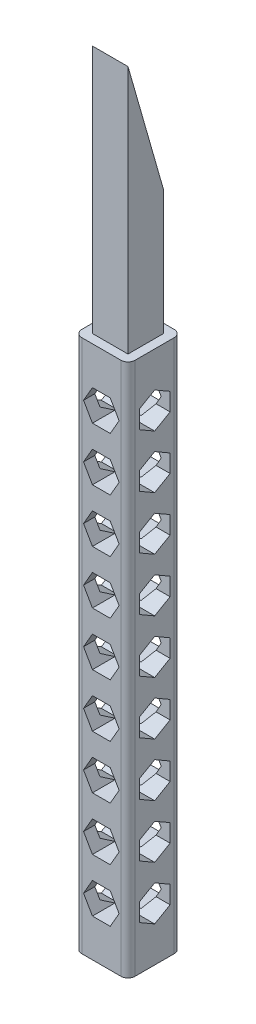
SolidWorks part; units mm, degrees
ref_plane "Front Plane" through (0, 0, 0) normal (0, 0, 1) x (1, 0, 0)
ref_plane "Top Plane" through (0, 0, 0) normal (0, 1, 0) x (1, 0, 0)
ref_plane "Right Plane" through (0, 0, 0) normal (1, 0, 0) x (0, 0, -1)
sketch "Sketch1" plane through (0, 0, 0) normal (0, 1, 0) x (1, 0, 0)
  line L1 (-7.5, -7.5) -> (7.5, -7.5)
  line L2 (-7.5, -7.5) -> (-7.5, 7.5)
  line L3 (-7.5, 7.5) -> (7.5, 7.5)
  line L4 (7.5, -7.5) -> (7.5, 7.5)
  line L5 (-7.5, -7.5) -> (7.5, 7.5) construction
  line L6 (-7.5, 7.5) -> (7.5, -7.5) construction
  point P0 (0, 0)
extrude "Boss-Extrude1" add sketch "Sketch1" along normal blind 150
sketch "Sketch3" plane through (0, 150, 0) normal (0, 1, 0) x (1, 0, 0)
  line L1 (-5, 5) -> (5, 5)
  line L2 (-5, 5) -> (-5, -5)
  line L3 (-5, -5) -> (5, -5)
  line L4 (5, 5) -> (5, -5)
  line L5 (-5, 5) -> (5, -5) construction
  line L6 (-5, -5) -> (5, 5) construction
  point P0 (0, 0)
extrude "Boss-Extrude2" add sketch "Sketch3" along normal blind 70
sketch "Sketch4" plane through (-5, 0, 0) normal (-1, 0, 0) x (0, 0, 1)
  line L0 (-5, 185) -> (5, 220)
  line L1 (-5, 220) -> (-5, 150) construction
  line L2 (-5, 185) -> (-5, 220)
  line L3 (-5, 220) -> (5, 220)
extrude "Cut-Extrude1" cut sketch "Sketch4" against normal blind 70
sketch "Sketch5" plane through (0, 0, -7.5) normal (0, 0, -1) x (-1, 0, 0)
  line L0 (0, 150) -> (0, 0) construction
  line L1 (-7.5, 150) -> (7.5, 150) construction
  line L2 (-7.5, 0) -> (7.5, 0) construction
  line L3 (5, 90) -> (2.5, 94.3301)
  line L4 (5, 75) -> (2.5, 79.3301)
  line L5 (2.5, 79.3301) -> (-2.5, 79.3301)
  line L6 (-2.5, 79.3301) -> (-5, 75)
  line L7 (-5, 75) -> (-2.5, 70.6699)
  line L8 (-2.5, 70.6699) -> (2.5, 70.6699)
  line L9 (2.5, 70.6699) -> (5, 75)
  line L10 (2.5, 94.3301) -> (-2.5, 94.3301)
  line L11 (-2.5, 94.3301) -> (-5, 90)
  line L12 (-5, 90) -> (-2.5, 85.6699)
  line L13 (-2.5, 85.6699) -> (2.5, 85.6699)
  line L14 (2.5, 85.6699) -> (5, 90)
  line L15 (5, 105) -> (2.5, 109.3301)
  line L16 (2.5, 109.3301) -> (-2.5, 109.3301)
  line L17 (-2.5, 109.3301) -> (-5, 105)
  line L18 (-5, 105) -> (-2.5, 100.6699)
  line L19 (-2.5, 100.6699) -> (2.5, 100.6699)
  line L20 (2.5, 100.6699) -> (5, 105)
  line L21 (5, 120) -> (2.5, 124.3301)
  line L22 (2.5, 124.3301) -> (-2.5, 124.3301)
  line L23 (-2.5, 124.3301) -> (-5, 120)
  line L24 (-5, 120) -> (-2.5, 115.6699)
  line L25 (-2.5, 115.6699) -> (2.5, 115.6699)
  line L26 (2.5, 115.6699) -> (5, 120)
  line L27 (5, 135) -> (2.5, 139.3301)
  line L28 (2.5, 139.3301) -> (-2.5, 139.3301)
  line L29 (-2.5, 139.3301) -> (-5, 135)
  line L30 (-5, 135) -> (-2.5, 130.6699)
  line L31 (-2.5, 130.6699) -> (2.5, 130.6699)
  line L32 (2.5, 130.6699) -> (5, 135)
  line L33 (5, 60) -> (2.5, 64.3301)
  line L34 (2.5, 64.3301) -> (-2.5, 64.3301)
  line L35 (-2.5, 64.3301) -> (-5, 60)
  line L36 (-5, 60) -> (-2.5, 55.6699)
  line L37 (-2.5, 55.6699) -> (2.5, 55.6699)
  line L38 (2.5, 55.6699) -> (5, 60)
  line L39 (5, 45) -> (2.5, 49.3301)
  line L40 (2.5, 49.3301) -> (-2.5, 49.3301)
  line L41 (-2.5, 49.3301) -> (-5, 45)
  line L42 (-5, 45) -> (-2.5, 40.6699)
  line L43 (-2.5, 40.6699) -> (2.5, 40.6699)
  line L44 (2.5, 40.6699) -> (5, 45)
  line L45 (5, 30) -> (2.5, 34.3301)
  line L46 (2.5, 34.3301) -> (-2.5, 34.3301)
  line L47 (-2.5, 34.3301) -> (-5, 30)
  line L48 (-5, 30) -> (-2.5, 25.6699)
  line L49 (-2.5, 25.6699) -> (2.5, 25.6699)
  line L50 (2.5, 25.6699) -> (5, 30)
  line L51 (5, 15) -> (2.5, 19.3301)
  line L52 (2.5, 19.3301) -> (-2.5, 19.3301)
  line L53 (-2.5, 19.3301) -> (-5, 15)
  line L54 (-5, 15) -> (-2.5, 10.6699)
  line L55 (-2.5, 10.6699) -> (2.5, 10.6699)
  line L56 (2.5, 10.6699) -> (5, 15)
  circle A0 centre (0, 75) radius 4.3301 construction
  circle A1 centre (0, 90) radius 4.3301 construction
  circle A2 centre (0, 105) radius 4.3301 construction
  circle A3 centre (0, 120) radius 4.3301 construction
  circle A4 centre (0, 135) radius 4.3301 construction
  circle A5 centre (0, 60) radius 4.3301 construction
  circle A6 centre (0, 45) radius 4.3301 construction
  circle A7 centre (0, 30) radius 4.3301 construction
  circle A8 centre (0, 15) radius 4.3301 construction
  dimension "D1" = 5
  dimension "D2" = 5
extrude "Cut-Extrude2" cut sketch "Sketch5" against normal blind 70
sketch "Sketch6" plane through (-7.5, 0, 0) normal (-1, 0, 0) x (0, 0, 1)
  line L0 (0, 85) -> (4.3301, 87.5)
  line L1 (0, 150) -> (0, 0) construction
  line L2 (-7.5, 150) -> (7.5, 150) construction
  line L3 (0, 70) -> (4.3301, 72.5)
  line L4 (4.3301, 72.5) -> (4.3301, 77.5)
  line L5 (4.3301, 77.5) -> (0, 80)
  line L6 (0, 80) -> (-4.3301, 77.5)
  line L7 (-4.3301, 77.5) -> (-4.3301, 72.5)
  line L8 (-4.3301, 72.5) -> (0, 70)
  line L9 (4.3301, 87.5) -> (4.3301, 92.5)
  line L10 (4.3301, 92.5) -> (0, 95)
  line L11 (0, 95) -> (-4.3301, 92.5)
  line L12 (-4.3301, 92.5) -> (-4.3301, 87.5)
  line L13 (-4.3301, 87.5) -> (0, 85)
  line L14 (0, 100) -> (4.3301, 102.5)
  line L15 (4.3301, 102.5) -> (4.3301, 107.5)
  line L16 (4.3301, 107.5) -> (0, 110)
  line L17 (0, 110) -> (-4.3301, 107.5)
  line L18 (-4.3301, 107.5) -> (-4.3301, 102.5)
  line L19 (-4.3301, 102.5) -> (0, 100)
  line L20 (0, 115) -> (4.3301, 117.5)
  line L21 (4.3301, 117.5) -> (4.3301, 122.5)
  line L22 (4.3301, 122.5) -> (0, 125)
  line L23 (0, 125) -> (-4.3301, 122.5)
  line L24 (-4.3301, 122.5) -> (-4.3301, 117.5)
  line L25 (-4.3301, 117.5) -> (0, 115)
  line L26 (0, 130) -> (4.3301, 132.5)
  line L27 (4.3301, 132.5) -> (4.3301, 137.5)
  line L28 (4.3301, 137.5) -> (0, 140)
  line L29 (0, 140) -> (-4.3301, 137.5)
  line L30 (-4.3301, 137.5) -> (-4.3301, 132.5)
  line L31 (-4.3301, 132.5) -> (0, 130)
  line L32 (0, 55) -> (4.3301, 57.5)
  line L33 (4.3301, 57.5) -> (4.3301, 62.5)
  line L34 (4.3301, 62.5) -> (0, 65)
  line L35 (0, 65) -> (-4.3301, 62.5)
  line L36 (-4.3301, 62.5) -> (-4.3301, 57.5)
  line L37 (-4.3301, 57.5) -> (0, 55)
  line L38 (0, 40) -> (4.3301, 42.5)
  line L39 (4.3301, 42.5) -> (4.3301, 47.5)
  line L40 (4.3301, 47.5) -> (0, 50)
  line L41 (0, 50) -> (-4.3301, 47.5)
  line L42 (-4.3301, 47.5) -> (-4.3301, 42.5)
  line L43 (-4.3301, 42.5) -> (0, 40)
  line L44 (0, 25) -> (4.3301, 27.5)
  line L45 (4.3301, 27.5) -> (4.3301, 32.5)
  line L46 (4.3301, 32.5) -> (0, 35)
  line L47 (0, 35) -> (-4.3301, 32.5)
  line L48 (-4.3301, 32.5) -> (-4.3301, 27.5)
  line L49 (-4.3301, 27.5) -> (0, 25)
  line L50 (0, 10) -> (4.3301, 12.5)
  line L51 (4.3301, 12.5) -> (4.3301, 17.5)
  line L52 (4.3301, 17.5) -> (0, 20)
  line L53 (0, 20) -> (-4.3301, 17.5)
  line L54 (-4.3301, 17.5) -> (-4.3301, 12.5)
  line L55 (-4.3301, 12.5) -> (0, 10)
  circle A0 centre (0, 75) radius 4.3301 construction
  circle A1 centre (0, 90) radius 4.3301 construction
  circle A2 centre (0, 105) radius 4.3301 construction
  circle A3 centre (0, 120) radius 4.3301 construction
  circle A4 centre (0, 135) radius 4.3301 construction
  circle A5 centre (0, 60) radius 4.3301 construction
  circle A6 centre (0, 45) radius 4.3301 construction
  circle A7 centre (0, 30) radius 4.3301 construction
  circle A8 centre (0, 15) radius 4.3301 construction
  dimension "D1" = 5
  dimension "D2" = 5
extrude "Cut-Extrude3" cut sketch "Sketch6" against normal blind 70
fillet "Fillet1" radius 2 4 edges at (-7.5, 75, 7.5) (7.5, 75, 7.5) (7.5, 75, -7.5) (-7.5, 75, -7.5)
